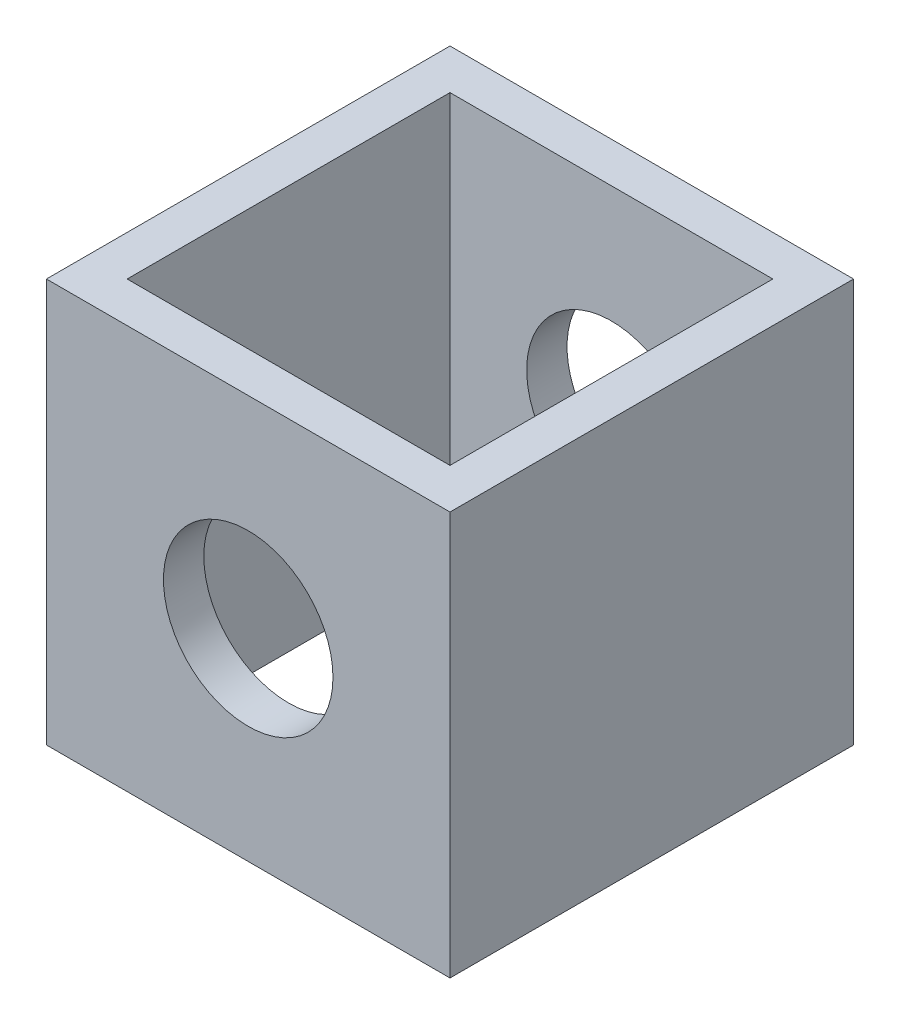
SolidWorks part; units mm, degrees
material "5052-H34"
ref_plane "正面" through (0, 0, 0) normal (0, 0, 1) x (1, 0, 0)
ref_plane "平面" through (0, 0, 0) normal (0, 1, 0) x (1, 0, 0)
ref_plane "右側面" through (0, 0, 0) normal (1, 0, 0) x (0, 0, -1)
sketch "ｽｹｯﾁ1" plane through (0, 0, 0) normal (0, 1, 0) x (1, 0, 0)
  line L1 (-5, 5) -> (5, 5)
  line L2 (-5, 5) -> (-5, -5)
  line L3 (-5, -5) -> (5, -5)
  line L4 (5, 5) -> (5, -5)
  line L5 (-5, 5) -> (5, -5) construction
  line L6 (-5, -5) -> (5, 5) construction
  point P0 (0, 0)
  dimension "D1" = 10
  dimension "D2" = 10
extrude "押し出し-薄板1" add sketch "ｽｹｯﾁ1" along normal blind 10 thin
sketch "ｽｹｯﾁ2" plane through (0, 0, 5) normal (0, 0, 1) x (1, 0, 0)
  line L0 (0, 10) -> (0, 0) construction
  line L1 (-5, 10) -> (5, 10) construction
  circle A0 centre (0, 5) radius 2.1
  dimension "D1" = 4.2
extrude "ｶｯﾄ - 押し出し1" cut sketch "ｽｹｯﾁ2" against normal through all
